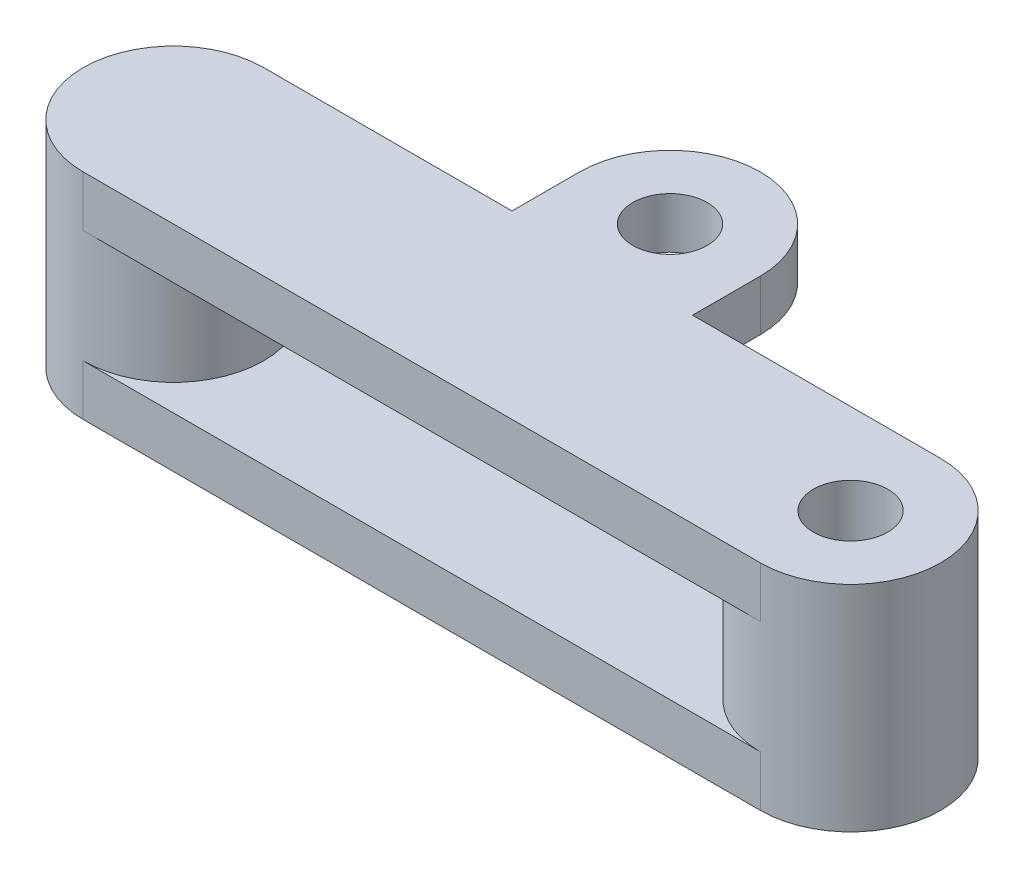
SolidWorks part; units mm, degrees
ref_plane "Front Plane" through (0, 0, 0) normal (0, 0, 1) x (1, 0, 0)
ref_plane "Top Plane" through (0, 0, 0) normal (0, 1, 0) x (1, 0, 0)
ref_plane "Right Plane" through (0, 0, 0) normal (1, 0, 0) x (0, 0, -1)
sketch "Sketch1" plane through (0, 0, 0) normal (0, 1, 0) x (1, 0, 0)
  line L0 (0, 0) -> (-30, 0) construction
  line L1 (0, -4) -> (-30, -4)
  line L2 (0, 4) -> (-11, 4)
  line L3 (-15, 7) -> (-15, 0) construction
  line L4 (-11, 7) -> (-11, 4)
  line L5 (-19, 7) -> (-19, 4)
  line L6 (-19, 4) -> (-30, 4)
  circle A0 centre (0, 0) radius 1.65
  arc A1 (0, -4) -> (0, 4) centre (0, 0) ccw
  arc A2 (-30, 4) -> (-30, -4) centre (-30, 0) ccw
  circle A3 centre (-15, 7) radius 1.65
  arc A4 (-11, 7) -> (-19, 7) centre (-15, 7) ccw
  point P4 (-15, 0)
  point P11 (-15, 0)
  point P14 (0, 0)
  point P16 (0, 0)
  point P17 (0, 0)
  point P19 (-15, 0)
  dimension "D1" = 3.3
  dimension "D2" = 4
  dimension "D4" = 4
  dimension "D5" = 3.3
  dimension "D3" = 30
  dimension "D6" = 3
extrude "Boss-Extrude1" add sketch "Sketch1" along normal blind 9.5
ref_plane "Plane1" through (0, 4.75, 0) normal (0, 1, 0) x (1, 0, 0)
sketch "Sketch2" plane through (0, 4.75, 0) normal (0, 1, 0) x (1, 0, 0)
  line L5 (0, 4) -> (-11, 4)
  line L6 (-11, 4) -> (-11, 7)
  line L7 (-19, 7) -> (-19, 4)
  line L8 (-19, 4) -> (-30, 4)
  line L9 (-30, -4) -> (0, -4)
  line L10 (0, 4) -> (-11, 4)
  line L11 (-11, 4) -> (-11, 7)
  line L12 (-19, 7) -> (-19, 4)
  line L13 (-19, 4) -> (-30, 4)
  line L14 (-30, -4) -> (0, -4)
  arc A0 (0, 4) -> (0, -4) centre (0, 0) ccw
  arc A1 (-30, -4) -> (-30, 4) centre (-30, 0) ccw
  arc A5 (0, -4) -> (0, 4) centre (0, 0) ccw
  arc A6 (-11, 7) -> (-19, 7) centre (-15, 7) ccw
  arc A7 (-30, 4) -> (-30, -4) centre (-30, 0) ccw
  arc A9 (-11, 7) -> (-19, 7) centre (-15, 7) ccw
  dimension "D1" = 0
extrude "Cut-Extrude1" cut sketch "Sketch2" against normal blind 2.5 and the other way blind 2.5
